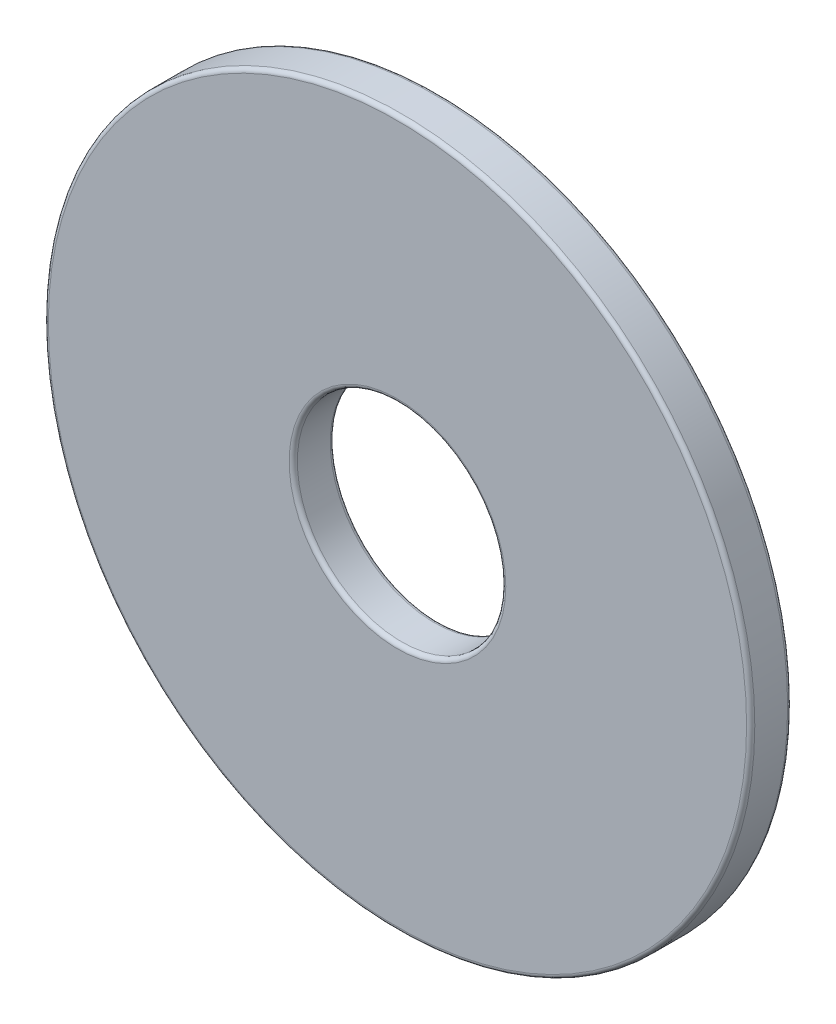
SolidWorks part; units mm, degrees
material "AISI 316 Stainless Steel Sheet (SS)"
ref_plane "Front Plane" through (0, 0, 0) normal (0, 0, 1) x (1, 0, 0)
ref_plane "Top Plane" through (0, 0, 0) normal (0, 1, 0) x (1, 0, 0)
ref_plane "Right Plane" through (0, 0, 0) normal (1, 0, 0) x (0, 0, -1)
sketch "Sketch1" plane through (0, 0, 0) normal (0, 0, 1) x (1, 0, 0)
  circle A0 centre (0, 0) radius 2.5781
  circle A1 centre (0, 0) radius 8.7376
  point P4 (0, 8.7376)
  point P5 (0, 2.5781)
  point P6 (0, -2.5781)
  point P7 (2.5781, 0)
  point P8 (-2.5781, 0)
  dimension "OD" = 17.4752
  dimension "ID" = 5.1562
sketch "Sketch2" plane through (0, 0, 0) normal (1, 0, 0) x (0, 0, -1)
  line L1 (-0.508, 8.7376) -> (0.508, 8.7376)
  line L2 (-0.508, 8.7376) -> (-0.508, -8.7376)
  line L3 (-0.508, -8.7376) -> (0.508, -8.7376)
  line L4 (0.508, 8.7376) -> (0.508, -8.7376)
  point P4 (0, 8.7376)
  point P5 (0.508, 0)
  dimension "Thickness" = 1.016
sketch "Sketch3" plane through (0, 0, 0) normal (0, 0, 1) x (1, 0, 0)
  circle A0 centre (0, 0) radius 2.5781 construction
  circle A1 centre (0, 0) radius 8.7376 construction
  circle A2 centre (0, 0) radius 2.5781
  circle A3 centre (0, 0) radius 8.7376
extrude "Boss-Extrude1" add sketch "Sketch3" against normal up to vertex (0.508 mm away) from vertex at 0.508 starting at point (0, 8.7376, 0.508)
fillet "Fillet1" radius 0.1016 4 edges at (2.5781, 0, 0.508) (2.5781, 0, -0.508) (8.7376, 0, 0.508) (8.7376, 0, -0.508)
equation "\"D1@Fillet1\"=\"Thickness@Sketch2\"*.1"
